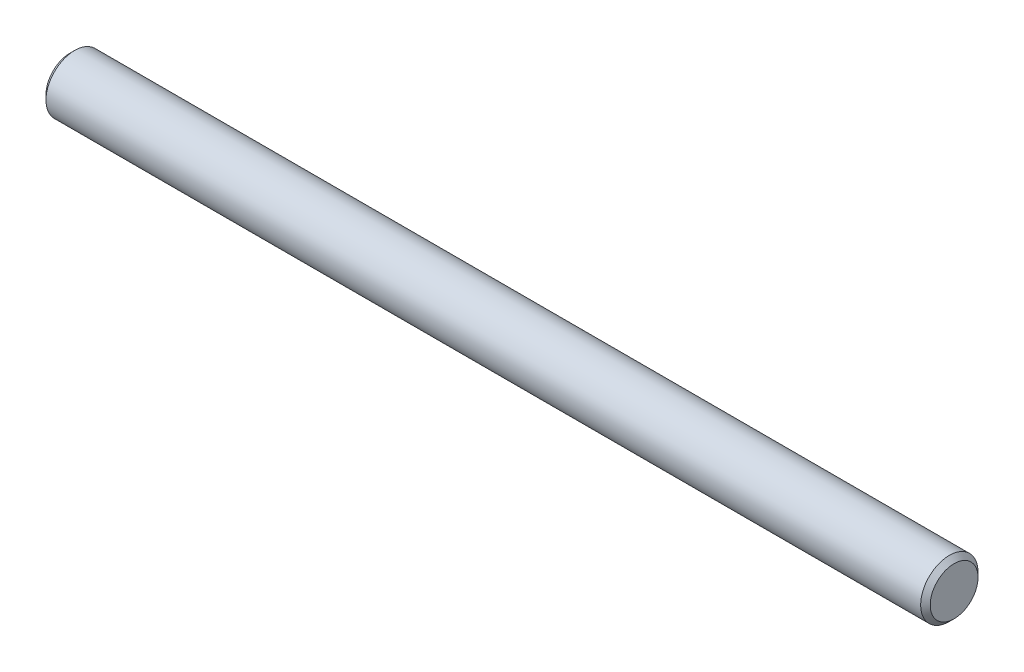
SolidWorks part; units mm, degrees
ref_plane "Спереди" through (0, 0, 0) normal (0, 0, 1) x (1, 0, 0)
ref_plane "Сверху" through (0, 0, 0) normal (0, 1, 0) x (1, 0, 0)
ref_plane "Справа" through (0, 0, 0) normal (1, 0, 0) x (0, 0, -1)
sketch "Эскиз1" plane through (0, 0, 0) normal (0, 0, 1) x (1, 0, 0)
  line L0 (-265.5371, 0) -> (13011.318, 0) construction
  line L1 (0, 0) -> (185, 0)
  line L2 (0, 0) -> (0, -6)
  line L3 (0, -6) -> (185, -6)
  line L4 (185, 0) -> (185, -6)
  dimension "D1" = 6
  dimension "D2" = 185
revolve "Повернуть2" add sketch "Эскиз1" angle 360 about L0
cosmetic thread "Условное изображение резьбы1" parameters "D1"=35, "D2"=10.344
cosmetic thread "Условное изображение резьбы2" parameters "D1"=70, "D2"=10.344
chamfer "Фаска1" distance 1 angle 45 2 edges at (185, 0, 6) (0, 0, 6)
